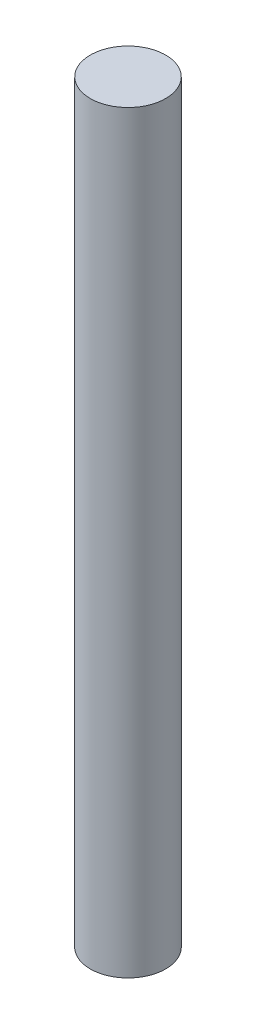
SolidWorks part; units mm, degrees
ref_plane "Front Plane" through (0, 0, 0) normal (0, 0, 1) x (1, 0, 0)
ref_plane "Top Plane" through (0, 0, 0) normal (0, 1, 0) x (1, 0, 0)
ref_plane "Right Plane" through (0, 0, 0) normal (1, 0, 0) x (0, 0, -1)
sketch "Sketch1" plane through (0, 0, 0) normal (0, 1, 0) x (1, 0, 0)
  circle A0 centre (-4.337, 0.8689) radius 0.5
  dimension "D1" = 1
extrude "Boss-Extrude1" add sketch "Sketch1" along normal blind 10
